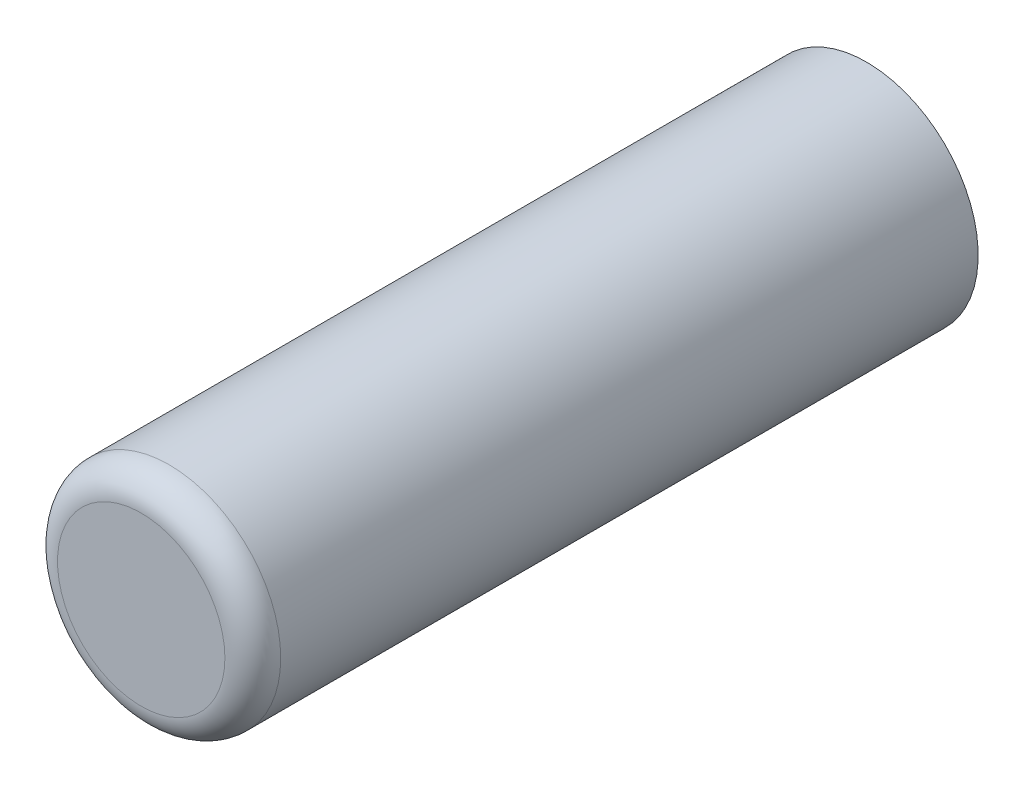
SolidWorks part; units mm, degrees
ref_plane "Front Plane" through (0, 0, 0) normal (0, 0, 1) x (1, 0, 0)
ref_plane "Top Plane" through (0, 0, 0) normal (0, 1, 0) x (1, 0, 0)
ref_plane "Right Plane" through (0, 0, 0) normal (1, 0, 0) x (0, 0, -1)
sketch "Sketch1" plane through (0, 0, 0) normal (0, 0, 1) x (1, 0, 0)
  circle A0 centre (0, 0) radius 2
extrude "Boss-Extrude1" add sketch "Sketch1" along normal blind 13
fillet "Fillet1" radius 0.5 1 edges at (2, 0, 13)
